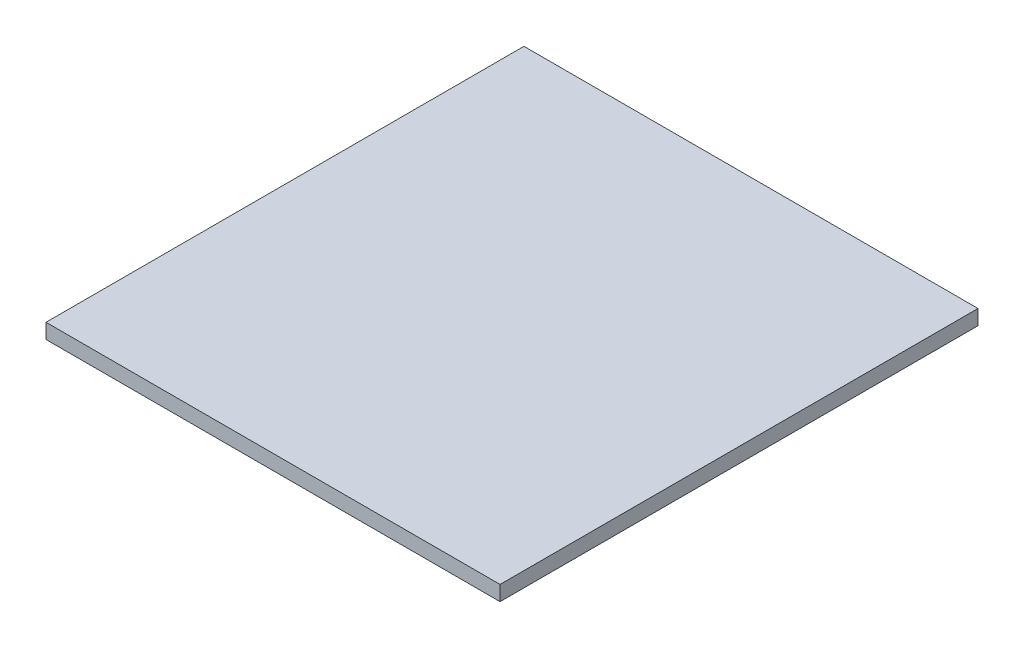
SolidWorks part; units mm, degrees
ref_plane "Front" through (0, 0, 0) normal (0, 0, 1) x (1, 0, 0)
ref_plane "Top" through (0, 0, 0) normal (0, 1, 0) x (1, 0, 0)
ref_plane "Right" through (0, 0, 0) normal (1, 0, 0) x (0, 0, -1)
sketch "Sketch1" plane through (0, 0, 0) normal (0, 1, 0) x (1, 0, 0)
  line L1 (0, 0) -> (96.52, 0)
  line L2 (0, 0) -> (0, 101.6)
  line L3 (0, 101.6) -> (96.52, 101.6)
  line L4 (96.52, 0) -> (96.52, 101.6)
  dimension "D1" = 96.52
  dimension "D2" = 101.6
extrude "Boss-Extrude1" add sketch "Sketch1" along normal blind 3.175
